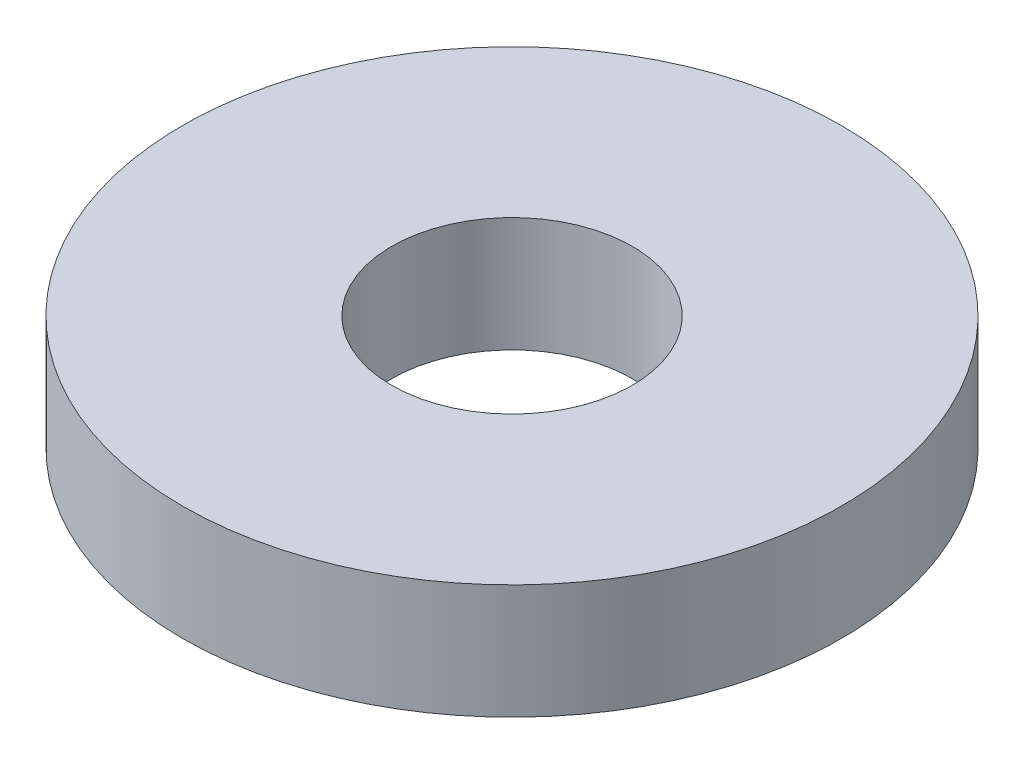
SolidWorks part; units mm, degrees
ref_plane "Front Plane" through (0, 0, 0) normal (0, 0, 1) x (1, 0, 0)
ref_plane "Top Plane" through (0, 0, 0) normal (0, 1, 0) x (1, 0, 0)
ref_plane "Right Plane" through (0, 0, 0) normal (1, 0, 0) x (0, 0, -1)
sketch "Sketch1" plane through (0, 0, 0) normal (0, 1, 0) x (1, 0, 0)
  circle A0 centre (0, 0) radius 5.75
  circle A1 centre (0, 0) radius 2.1
  dimension "D1" = 4.2
  dimension "D2" = 11.5
extrude "Boss-Extrude1" add sketch "Sketch1" along normal blind 2
